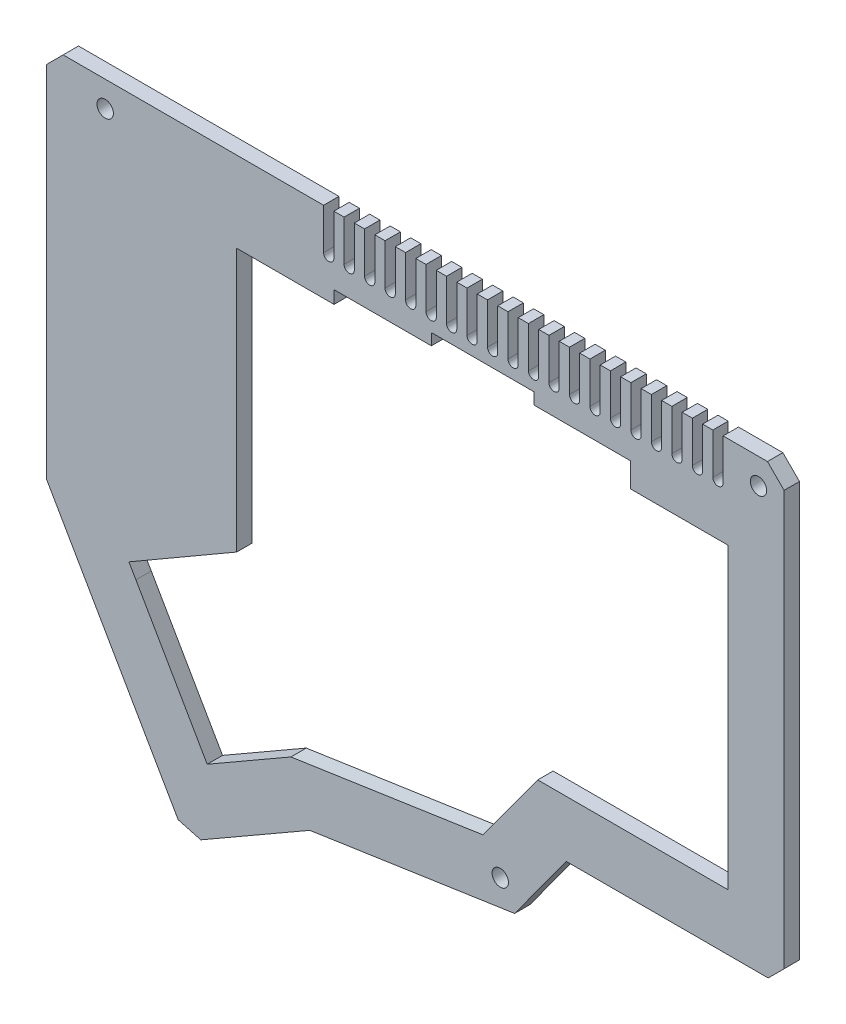
SolidWorks part; units mm, degrees
ref_plane "Plan de face" through (0, 0, 0) normal (0, 0, 1) x (1, 0, 0)
ref_plane "Plan de dessus" through (0, 0, 0) normal (0, 1, 0) x (1, 0, 0)
ref_plane "Plan de droite" through (0, 0, 0) normal (1, 0, 0) x (0, 0, -1)
sketch "Esquisse1" plane through (0, 0, 0) normal (0, 0, 1) x (1, 0, 0)
  line L0 (-117.3419, -15.4198) -> (-103.3409, -15.4198) construction
  line L1 (-103.3409, -15.4198) -> (-103.3409, -29.4208) construction
  line L2 (-103.3409, -29.4208) -> (-117.3419, -29.4208) construction
  line L3 (-117.3419, -29.4208) -> (-117.3419, -15.4198) construction
  line L4 (-98.3406, -27.0457) -> (-98.3406, -13.0447) construction
  line L5 (-98.3406, -13.0447) -> (-84.3396, -13.0447) construction
  line L6 (-84.3396, -13.0447) -> (-84.3396, -27.0457) construction
  line L7 (-84.3396, -27.0457) -> (-98.3406, -27.0457) construction
  line L8 (-79.3392, -24.6705) -> (-79.3392, -10.6695) construction
  line L9 (-79.3392, -10.6695) -> (-65.3382, -10.6695) construction
  line L10 (-65.3382, -10.6695) -> (-65.3382, -24.6705) construction
  line L11 (-65.3382, -24.6705) -> (-79.3392, -24.6705) construction
  line L12 (-60.3379, -27.0457) -> (-60.3379, -13.0447) construction
  line L13 (-60.3379, -13.0447) -> (-46.3369, -13.0447) construction
  line L14 (-46.3369, -13.0447) -> (-46.3369, -27.0457) construction
  line L15 (-46.3369, -27.0457) -> (-60.3379, -27.0457) construction
  line L16 (-41.3365, -31.796) -> (-41.3365, -17.795) construction
  line L17 (-41.3365, -17.795) -> (-27.3355, -17.795) construction
  line L18 (-27.3355, -17.795) -> (-27.3355, -31.796) construction
  line L19 (-27.3355, -31.796) -> (-41.3365, -31.796) construction
  line L20 (-22.3347, -31.796) -> (-22.3347, -17.795) construction
  line L21 (-22.3347, -17.795) -> (-8.3337, -17.795) construction
  line L22 (-8.3337, -17.795) -> (-8.3337, -31.796) construction
  line L23 (-8.3337, -31.796) -> (-22.3347, -31.796) construction
  line L24 (-117.3419, -34.4212) -> (-103.3409, -34.4212) construction
  line L25 (-103.3409, -34.4212) -> (-103.3409, -48.4222) construction
  line L26 (-103.3409, -48.4222) -> (-117.3419, -48.4222) construction
  line L27 (-117.3419, -48.4222) -> (-117.3419, -34.4212) construction
  line L28 (-98.3406, -32.046) -> (-84.3396, -32.046) construction
  line L29 (-84.3396, -32.046) -> (-84.3396, -46.047) construction
  line L30 (-84.3396, -46.047) -> (-98.3406, -46.047) construction
  line L31 (-98.3406, -46.047) -> (-98.3406, -32.046) construction
  line L32 (-79.3392, -29.6709) -> (-65.3382, -29.6709) construction
  line L33 (-65.3382, -29.6709) -> (-65.3382, -43.6718) construction
  line L34 (-65.3382, -43.6718) -> (-79.3392, -43.6718) construction
  line L35 (-79.3392, -43.6718) -> (-79.3392, -29.6709) construction
  line L36 (-60.3379, -32.046) -> (-46.3369, -32.046) construction
  line L37 (-46.3369, -32.046) -> (-46.3369, -46.047) construction
  line L38 (-46.3369, -46.047) -> (-60.3379, -46.047) construction
  line L39 (-60.3379, -46.047) -> (-60.3379, -32.046) construction
  line L40 (-41.3365, -36.7964) -> (-27.3355, -36.7964) construction
  line L41 (-27.3355, -36.7964) -> (-27.3355, -50.7973) construction
  line L42 (-27.3355, -50.7973) -> (-41.3365, -50.7973) construction
  line L43 (-41.3365, -50.7973) -> (-41.3365, -36.7964) construction
  line L44 (-22.3347, -36.7964) -> (-8.3337, -36.7964) construction
  line L45 (-8.3337, -36.7964) -> (-8.3337, -50.7973) construction
  line L46 (-8.3337, -50.7973) -> (-22.3347, -50.7973) construction
  line L47 (-22.3347, -50.7973) -> (-22.3347, -36.7964) construction
  line L48 (-22.3347, -55.7977) -> (-8.3337, -55.7977) construction
  line L49 (-8.3337, -55.7977) -> (-8.3337, -69.7987) construction
  line L50 (-8.3337, -69.7987) -> (-22.3347, -69.7987) construction
  line L51 (-22.3347, -69.7987) -> (-22.3347, -55.7977) construction
  line L52 (-41.3365, -55.7977) -> (-27.3355, -55.7977) construction
  line L53 (-27.3355, -55.7977) -> (-27.3355, -69.7987) construction
  line L54 (-27.3355, -69.7987) -> (-41.3365, -69.7987) construction
  line L55 (-41.3365, -69.7987) -> (-41.3365, -55.7977) construction
  line L56 (-60.3379, -51.0474) -> (-46.3369, -51.0474) construction
  line L57 (-46.3369, -51.0474) -> (-46.3369, -65.0484) construction
  line L58 (-46.3369, -65.0484) -> (-60.3379, -65.0484) construction
  line L59 (-60.3379, -65.0484) -> (-60.3379, -51.0474) construction
  line L60 (-79.3392, -48.6722) -> (-65.3382, -48.6722) construction
  line L61 (-65.3382, -48.6722) -> (-65.3382, -62.6732) construction
  line L62 (-65.3382, -62.6732) -> (-79.3392, -62.6732) construction
  line L63 (-79.3392, -62.6732) -> (-79.3392, -48.6722) construction
  line L64 (-98.3406, -51.0474) -> (-84.3396, -51.0474) construction
  line L65 (-84.3396, -51.0474) -> (-84.3396, -65.0484) construction
  line L66 (-84.3396, -65.0484) -> (-98.3406, -65.0484) construction
  line L67 (-98.3406, -65.0484) -> (-98.3406, -51.0474) construction
  line L68 (-117.3419, -53.4225) -> (-103.3409, -53.4225) construction
  line L69 (-103.3409, -53.4225) -> (-103.3409, -67.4235) construction
  line L70 (-103.3409, -67.4235) -> (-117.3419, -67.4235) construction
  line L71 (-117.3419, -67.4235) -> (-117.3419, -53.4225) construction
  line L72 (-88.8399, -70.6738) -> (-74.8389, -70.6738) construction
  line L73 (-74.8389, -70.6738) -> (-74.8389, -84.6747) construction
  line L74 (-74.8389, -84.6747) -> (-88.8399, -84.6747) construction
  line L75 (-88.8399, -84.6747) -> (-88.8399, -70.6738) construction
  line L76 (-111.4175, -75.4665) -> (-97.8899, -71.8565) construction
  line L77 (-97.8899, -71.8565) -> (-94.28, -85.3841) construction
  line L78 (-94.28, -85.3841) -> (-107.8075, -88.9941) construction
  line L79 (-107.8075, -88.9941) -> (-111.4175, -75.4665) construction
  line L80 (-134.6581, -81.5997) -> (-122.5281, -74.6075) construction
  line L81 (-122.5281, -74.6075) -> (-115.5359, -86.7375) construction
  line L82 (-115.5359, -86.7375) -> (-127.6659, -93.7297) construction
  line L83 (-127.6659, -93.7297) -> (-134.6581, -81.5997) construction
  line L86 (-6.475, -71.9336) -> (-62.0853, -71.9336) construction
  line L89 (-72.824, -86.6446) -> (-62.0853, -71.9336) construction
  line L96 (-109.7697, -91.4639) -> (-73.0906, -86.6918) construction
  line L97 (-124.664, -99.8297) -> (-110.3971, -91.5881) construction
  line L98 (-139.9408, -76.5013) -> (-126.7151, -99.4281) construction
  line L99 (-119.8527, -15.5421) -> (-139.6028, -15.5421) construction
  line L100 (-100.8528, -13.2921) -> (-118.8527, -13.2921) construction
  line L101 (-63.8455, -8.5421) -> (-80.8528, -8.5421) construction
  line L102 (-44.8455, -10.792) -> (-62.8485, -10.792) construction
  line L103 (-25.8456, -15.5421) -> (-43.8486, -15.5421) construction
  line L104 (-6.8456, -15.5421) -> (-23.8529, -15.5421) construction
  line L105 (-6.2741, -71.3672) -> (-6.2741, -16.1136) construction
  line L106 (-23.8529, -71.9423) -> (-6.8456, -71.9423) construction
  line L107 (-61.8455, -71.9423) -> (-25.8456, -71.9423) construction
  line L108 (-72.6738, -86.4911) -> (-62.1363, -72.0583) construction
  line L109 (-140.1743, -16.1136) -> (-140.1743, -75.5958) construction
  line L110 (-134.3462, 1.5705) -> (-134.3466, -55.7217) construction
  line L111 (-134.3466, -55.7217) -> (-160.479, -70.8411) construction
  line L112 (-160.479, -70.8411) -> (-133.7613, -117.344) construction
  line L113 (-126.937, -119.1852) -> (-105.0783, -106.604) construction
  line L114 (-105.0783, -106.604) -> (-64.4097, -100.5586) construction
  line L115 (-64.4097, -100.5586) -> (-54.4636, -86.9336) construction
  line L116 (3.6609, -86.9336) -> (-54.4636, -86.9336) construction
  line L117 (-10.475, -82.0685) -> (-10.475, 1.3161) construction
  line L122 (3.525, 6.3153) -> (-96.3444, 6.3209) construction
  line L129 (8.525, -86.9336) -> (8.525, -0.6796) construction
  line L130 (-48.3431, 6.3182) -> (-96.3444, 6.3209) construction
  line L131 (-115.3458, 1.5705) -> (-134.3462, 1.5705) construction
  line L132 (-160.479, -3.4295) -> (-160.479, -70.8411) construction
  line L135 (-119.3466, -64.3728) -> (-135.695, -73.8315) construction
  line L136 (-140.0228, -76.3355) -> (-140.0228, -76.3321)
  line L138 (-160.479, -70.8411) -> (-131.2704, -121.6794) construction
  line L139 (-131.2704, -121.6794) -> (-105.0783, -106.604) construction
  line L140 (-133.7613, -117.344) -> (-126.937, -119.1852) construction
  line L142 (-10.475, 1.3161) -> (-15.475, 6.3164) construction
  line L143 (8.525, -86.9336) -> (-54.4636, -86.9336) construction
  line L144 (-10.475, -82.0685) -> (-15.3391, -86.9326) construction
  line L148 (-103.3409, 6.3209) -> (-119.3463, 6.3209) construction
  line L149 (-119.3463, 6.3209) -> (-119.3463, 1.5705) construction
  line L150 (-140.0228, 1.5705) -> (-140.0228, 6.3209) construction
  line L151 (-140.0228, 6.3209) -> (-155.479, 6.3209) construction
  line L152 (-160.479, 1.3209) -> (-160.479, -3.4295) construction
  line L153 (-155.479, 6.3209) -> (-160.479, 1.3209) construction
  line L154 (8.525, -1.685) -> (-119.3463, -1.6779) construction
  line L155 (-146.0924, -79.8227) -> (-128.3223, -110.752) construction
  line L156 (-128.3223, -110.752) -> (-107.7547, -98.9139) construction
  line L157 (-140.0228, -78.3428) -> (-126.1111, -102.5565)
  line L158 (-126.1111, -102.5565) -> (-109.762, -93.1464)
  line L159 (-109.762, -93.1464) -> (-72.2631, -87.5722)
  line L160 (-72.2631, -87.5722) -> (-61.5772, -72.9336)
  line L162 (-24.475, -72.9336) -> (-24.475, -14.6796)
  line L163 (-24.475, -14.6796) -> (-43.4777, -14.6796)
  line L164 (-43.4777, -14.6796) -> (-43.4777, -9.9293)
  line L165 (-43.4777, -9.9293) -> (-62.3431, -9.9293)
  line L166 (-62.3431, -9.9293) -> (-62.3431, -7.681)
  line L167 (-62.3431, -7.681) -> (-82.3444, -7.6799)
  line L168 (-82.3444, -7.6799) -> (-82.3444, -9.9293)
  line L169 (-82.3444, -9.9293) -> (-101.3458, -9.9293)
  line L170 (-101.3458, -9.9293) -> (-101.3458, -12.4295)
  line L171 (-101.3458, -12.4295) -> (-120.3463, -12.4295)
  line L172 (-120.3463, -12.4295) -> (-120.3466, -63.7961)
  line L173 (-120.3466, -63.7961) -> (-140.5236, -75.4699)
  line L174 (-107.7547, -98.9139) -> (-68.8973, -93.1378) construction
  line L175 (-68.8973, -93.1378) -> (-58.5285, -78.9336) construction
  line L176 (0.525, -78.9336) -> (-58.5285, -78.9336) construction
  line L177 (-18.475, -78.9336) -> (-18.475, -1.6845) construction
  line L178 (-62.3428, -1.681) -> (-82.3441, -1.6799) construction
  line L179 (0.525, -78.9336) -> (0.525, -14.6796) construction
  line L180 (-146.0228, -76.3355) -> (-146.0228, 1.5705) construction
  line L181 (-140.0228, -76.3355) -> (-140.0228, 1.5705) construction
  line L182 (-135.695, -73.8315) -> (-140.0228, -71.3355) construction
  line L185 (-16.7232, 3.3209) -> (-116.3463, 3.3209)
  line L186 (-116.3463, 3.3209) -> (-116.3463, 1.5705) construction
  line L187 (-116.3463, 1.5705) -> (-116.3466, -66.103) construction
  line L188 (-116.3466, -66.103) -> (-135.6926, -77.2961) construction
  line L189 (-135.6926, -77.2961) -> (-143.0228, -73.0684) construction
  line L190 (-143.0228, -73.0684) -> (-143.0228, 1.5705) construction
  line L191 (-143.0228, 1.5705) -> (-143.0228, 3.3209) construction
  line L192 (-143.0228, 3.3209) -> (-154.2363, 3.3209)
  line L193 (-154.2363, 3.3209) -> (-157.479, 0.0782)
  line L194 (-157.479, 0.0782) -> (-157.479, -3.4295)
  line L195 (-157.479, -3.4295) -> (-157.479, -70.0407)
  line L196 (-157.479, -70.0407) -> (-131.7794, -114.7715)
  line L197 (-131.7794, -114.7715) -> (-127.3559, -115.9649)
  line L198 (-127.3559, -115.9649) -> (-106.082, -103.7202)
  line L199 (-106.082, -103.7202) -> (-66.0925, -97.7758)
  line L200 (-66.0925, -97.7758) -> (-55.988, -83.9336)
  line L201 (-16.5817, -83.9336) -> (-55.988, -83.9336)
  line L202 (-13.475, -80.8269) -> (-16.5817, -83.9336)
  line L203 (-13.475, -80.8269) -> (-13.475, 0.0724)
  line L204 (-13.475, 0.0724) -> (-16.7232, 3.3209)
  line L205 (-143.0228, 3.3209) -> (-140.0228, 3.3209)
  line L206 (-140.8899, -76.8336) -> (-119.3466, -64.3728) construction
  line L207 (-140.0228, -71.3355) -> (-140.0228, 1.5705) construction
  line L208 (-119.3463, 3.3209) -> (-116.3463, 3.3209)
  line L209 (-140.8899, -76.8336) -> (-126.1111, -102.5565) construction
  line L210 (-119.3463, 1.5705) -> (-119.3466, -64.3728) construction
  line L211 (-101.3458, -12.4295) -> (-120.3463, -12.4295) construction
  line L212 (-119.3463, 3.3209) -> (-140.0228, 3.3209)
  line L213 (-120.3463, -12.4295) -> (-120.3466, -64.3728) construction
  line L217 (-6.475, -71.9336) -> (-6.475, -15.6796) construction
  line L220 (-6.475, -15.6796) -> (-44.4777, -15.6796) construction
  line L221 (-44.4777, -15.6796) -> (-44.4777, -10.9293) construction
  line L222 (-44.4777, -10.9293) -> (-63.3431, -10.9293) construction
  line L223 (-63.3431, -10.9293) -> (-63.3431, -8.681) construction
  line L224 (-63.3431, -8.681) -> (-81.3444, -8.68) construction
  line L225 (-81.3444, -8.68) -> (-81.3444, -10.9293) construction
  line L226 (-81.3444, -10.9293) -> (-100.3458, -10.9293) construction
  line L227 (-100.3458, -10.9293) -> (-100.3458, -13.4295) construction
  line L228 (-100.3458, -13.4295) -> (-119.3463, -13.4295) construction
  line L231 (-119.3463, -13.4295) -> (-119.3466, -64.3728) construction
  line L232 (-119.3466, -64.3728) -> (-140.0228, -76.3355) construction
  line L233 (-140.0228, -76.3355) -> (-125.7426, -101.1906) construction
  line L234 (-125.7426, -101.1906) -> (-110.0965, -92.1851) construction
  line L235 (-110.0965, -92.1851) -> (-72.824, -86.6446) construction
  line L236 (-140.0228, -71.3355) -> (-140.0228, -59.0058)
  line L237 (-119.8474, -63.5072) -> (-140.5236, -75.4699) construction
  line L238 (-140.5236, -75.4699) -> (-141.4072, -75.9811)
  line L239 (-141.4072, -75.9811) -> (-140.0228, -78.3428)
  line L240 (-13.475, -5.3532) -> (-25.475, -5.3532) construction
  line L241 (-6.475, 3.3159) -> (-6.475, -6.6841) construction
  line L242 (5.525, 0.0724) -> (2.2822, 3.3154) construction
  line L245 (-5.475, -72.9336) -> (-5.475, -14.6796) construction
  line L248 (8.525, -82.0695) -> (3.6609, -86.9336) construction
  line L251 (5.525, -80.8269) -> (2.4183, -83.9336) construction
  line L254 (8.525, -82.0695) -> (8.525, 1.315) construction
  line L257 (5.525, -80.8269) -> (5.525, 0.0724) construction
  line L260 (8.525, 1.315) -> (3.525, 6.3153) construction
  line L263 (-24.475, -72.9336) -> (-61.5772, -72.9336)
  line L266 (-5.475, -14.6796) -> (-43.4777, -14.6796) construction
  line L269 (2.4183, -83.9336) -> (-55.988, -83.9336) construction
  line L275 (-5.475, -72.9336) -> (-61.5772, -72.9336) construction
  line L322 (-103.3409, 3.3209) -> (-96.3445, 3.3209) construction
  line L323 (-103.3409, 3.3209) -> (-116.3463, 3.3209) construction
  line L328 (-48.3431, 4.0707) -> (-48.3431, 6.3182) construction
  line L329 (-29.4777, 4.0707) -> (-48.3431, 4.0707) construction
  line L330 (-29.4777, -0.6796) -> (-29.4777, 4.0707) construction
  line L331 (8.525, -0.6796) -> (-29.4777, -0.6796) construction
  line L332 (-115.3458, 4.0707) -> (-115.3458, 1.5705) construction
  line L333 (-96.3444, 4.0707) -> (-115.3458, 4.0707) construction
  line L334 (-96.3444, 6.3209) -> (-96.3444, 4.0707) construction
  line L343 (2.2822, 3.3154) -> (-96.3445, 3.3209) construction
  line L465 (-103.3409, 6.3209) -> (-96.3444, 6.3209) construction
  circle A2 centre (-18.475, -1.6845) radius 1.6
  circle A3 centre (-18.475, -1.6845) radius 3 construction
  circle A4 centre (-110.3971, -1.6784) radius 1.6 construction
  circle A5 centre (-18.475, -78.9336) radius 1.6 construction
  circle A6 centre (-68.8973, -93.1378) radius 1.6
  circle A7 centre (-128.3223, -110.752) radius 1.6 construction
  circle A8 centre (-146.0924, -79.8227) radius 1.6 construction
  circle A9 centre (-146.0228, -1.6779) radius 1.6
  circle A10 centre (-110.3971, -1.6784) radius 3 construction
  circle A11 centre (-146.0228, -1.6779) radius 3 construction
  circle A12 centre (-146.0924, -79.8227) radius 3 construction
  circle A13 centre (-128.3223, -110.752) radius 3 construction
  circle A14 centre (-68.8973, -93.1378) radius 3 construction
  circle A15 centre (-18.475, -78.9336) radius 3 construction
  point P138 (-160.479, 1.5705)
  point P139 (-10.475, 6.3161)
  point P150 (-160.479, 6.3209)
  dimension "D3" = 3.2
  dimension "D4" = 6
  dimension "D6" = 3.2
  dimension "D7" = 3.2
  dimension "D8" = 3.2
  dimension "D9" = 3.2
  dimension "D10" = 3.2
  dimension "D15" = 3.2
  dimension "D17" = 12
  dimension "D1" = 15
  dimension "D5" = 1
  dimension "D13" = 6
  dimension "D16" = 3
extrude "Boss.-Extru.1" add sketch "Esquisse1" along normal blind 3
sketch "Esquisse2" plane through (0, 0, 3) normal (0, 0, 1) x (1, 0, 0)
  line L19 (-26.3866, 6.0542) -> (-26.3866, -4.6791) construction
  line L20 (-25.3866, 6.0542) -> (-25.3866, -4.6791)
  line L21 (-27.3866, 6.0542) -> (-27.3866, -4.6791)
  line L22 (-30.3866, 6.0542) -> (-30.3866, -4.6791) construction
  line L23 (-29.3866, 6.0542) -> (-29.3866, -4.6791)
  line L24 (-31.3866, 6.0542) -> (-31.3866, -4.6791)
  line L25 (-34.3866, 6.0542) -> (-34.3866, -4.6791) construction
  line L26 (-33.3866, 6.0542) -> (-33.3866, -4.6791)
  line L27 (-35.3866, 6.0542) -> (-35.3866, -4.6791)
  line L28 (-38.3866, 6.0542) -> (-38.3866, -4.6791) construction
  line L29 (-37.3866, 6.0542) -> (-37.3866, -4.6791)
  line L30 (-39.3866, 6.0542) -> (-39.3866, -4.6791)
  line L31 (-42.3866, 6.0542) -> (-42.3866, -4.6791) construction
  line L32 (-41.3866, 6.0542) -> (-41.3866, -4.6791)
  line L33 (-43.3866, 6.0542) -> (-43.3866, -4.6791)
  line L34 (-46.3866, 6.0542) -> (-46.3866, -4.6791) construction
  line L35 (-45.3866, 6.0542) -> (-45.3866, -4.6791)
  line L36 (-47.3866, 6.0542) -> (-47.3866, -4.6791)
  line L37 (-50.3866, 6.0542) -> (-50.3866, -4.6791) construction
  line L38 (-49.3866, 6.0542) -> (-49.3866, -4.6791)
  line L39 (-51.3866, 6.0542) -> (-51.3866, -4.6791)
  line L40 (-54.3866, 6.0542) -> (-54.3866, -4.6791) construction
  line L41 (-53.3866, 6.0542) -> (-53.3866, -4.6791)
  line L42 (-55.3866, 6.0542) -> (-55.3866, -4.6791)
  line L43 (-58.3866, 6.0542) -> (-58.3866, -4.6791) construction
  line L44 (-57.3866, 6.0542) -> (-57.3866, -4.6791)
  line L45 (-59.3866, 6.0542) -> (-59.3866, -4.6791)
  line L46 (-62.3866, 6.0542) -> (-62.3866, -4.6791) construction
  line L47 (-61.3866, 6.0542) -> (-61.3866, -4.6791)
  line L48 (-63.3866, 6.0542) -> (-63.3866, -4.6791)
  line L49 (-66.3866, 6.0542) -> (-66.3866, -4.6791) construction
  line L50 (-65.3866, 6.0542) -> (-65.3866, -4.6791)
  line L51 (-67.3866, 6.0542) -> (-67.3866, -4.6791)
  line L52 (-70.3866, 6.0542) -> (-70.3866, -4.6791) construction
  line L53 (-69.3866, 6.0542) -> (-69.3866, -4.6791)
  line L54 (-71.3866, 6.0542) -> (-71.3866, -4.6791)
  line L55 (-74.3866, 6.0542) -> (-74.3866, -4.6791) construction
  line L56 (-73.3866, 6.0542) -> (-73.3866, -4.6791)
  line L57 (-75.3866, 6.0542) -> (-75.3866, -4.6791)
  line L58 (-78.3866, 6.0542) -> (-78.3866, -4.6791) construction
  line L59 (-77.3866, 6.0542) -> (-77.3866, -4.6791)
  line L60 (-79.3866, 6.0542) -> (-79.3866, -4.6791)
  line L61 (-82.3866, 6.0542) -> (-82.3866, -4.6791) construction
  line L62 (-81.3866, 6.0542) -> (-81.3866, -4.6791)
  line L63 (-83.3866, 6.0542) -> (-83.3866, -4.6791)
  line L64 (-86.3866, 6.0542) -> (-86.3866, -4.6791) construction
  line L65 (-85.3866, 6.0542) -> (-85.3866, -4.6791)
  line L66 (-87.3866, 6.0542) -> (-87.3866, -4.6791)
  line L67 (-90.3866, 6.0542) -> (-90.3866, -4.6791) construction
  line L68 (-89.3866, 6.0542) -> (-89.3866, -4.6791)
  line L69 (-91.3866, 6.0542) -> (-91.3866, -4.6791)
  line L70 (-94.3866, 6.0542) -> (-94.3866, -4.6791) construction
  line L71 (-93.3866, 6.0542) -> (-93.3866, -4.6791)
  line L72 (-95.3866, 6.0542) -> (-95.3866, -4.6791)
  line L73 (-98.3866, 6.0542) -> (-98.3866, -4.6791) construction
  line L74 (-97.3866, 6.0542) -> (-97.3866, -4.6791)
  line L75 (-99.3866, 6.0542) -> (-99.3866, -4.6791)
  line L76 (-102.3866, 6.0542) -> (-102.3866, -4.6791) construction
  line L77 (-101.3866, 6.0542) -> (-101.3866, -4.6791)
  line L78 (-103.3866, 6.0542) -> (-103.3866, -4.6791)
  arc A10 (-25.3866, 6.0542) -> (-27.3866, 6.0542) centre (-26.3866, 6.0542) ccw
  arc A11 (-27.3866, -4.6791) -> (-25.3866, -4.6791) centre (-26.3866, -4.6791) ccw
  arc A12 (-29.3866, 6.0542) -> (-31.3866, 6.0542) centre (-30.3866, 6.0542) ccw
  arc A13 (-31.3866, -4.6791) -> (-29.3866, -4.6791) centre (-30.3866, -4.6791) ccw
  arc A14 (-33.3866, 6.0542) -> (-35.3866, 6.0542) centre (-34.3866, 6.0542) ccw
  arc A15 (-35.3866, -4.6791) -> (-33.3866, -4.6791) centre (-34.3866, -4.6791) ccw
  arc A16 (-37.3866, 6.0542) -> (-39.3866, 6.0542) centre (-38.3866, 6.0542) ccw
  arc A17 (-39.3866, -4.6791) -> (-37.3866, -4.6791) centre (-38.3866, -4.6791) ccw
  arc A18 (-41.3866, 6.0542) -> (-43.3866, 6.0542) centre (-42.3866, 6.0542) ccw
  arc A19 (-43.3866, -4.6791) -> (-41.3866, -4.6791) centre (-42.3866, -4.6791) ccw
  arc A20 (-45.3866, 6.0542) -> (-47.3866, 6.0542) centre (-46.3866, 6.0542) ccw
  arc A21 (-47.3866, -4.6791) -> (-45.3866, -4.6791) centre (-46.3866, -4.6791) ccw
  arc A22 (-49.3866, 6.0542) -> (-51.3866, 6.0542) centre (-50.3866, 6.0542) ccw
  arc A23 (-51.3866, -4.6791) -> (-49.3866, -4.6791) centre (-50.3866, -4.6791) ccw
  arc A24 (-53.3866, 6.0542) -> (-55.3866, 6.0542) centre (-54.3866, 6.0542) ccw
  arc A25 (-55.3866, -4.6791) -> (-53.3866, -4.6791) centre (-54.3866, -4.6791) ccw
  arc A26 (-57.3866, 6.0542) -> (-59.3866, 6.0542) centre (-58.3866, 6.0542) ccw
  arc A27 (-59.3866, -4.6791) -> (-57.3866, -4.6791) centre (-58.3866, -4.6791) ccw
  arc A28 (-61.3866, 6.0542) -> (-63.3866, 6.0542) centre (-62.3866, 6.0542) ccw
  arc A29 (-63.3866, -4.6791) -> (-61.3866, -4.6791) centre (-62.3866, -4.6791) ccw
  arc A30 (-65.3866, 6.0542) -> (-67.3866, 6.0542) centre (-66.3866, 6.0542) ccw
  arc A31 (-67.3866, -4.6791) -> (-65.3866, -4.6791) centre (-66.3866, -4.6791) ccw
  arc A32 (-69.3866, 6.0542) -> (-71.3866, 6.0542) centre (-70.3866, 6.0542) ccw
  arc A33 (-71.3866, -4.6791) -> (-69.3866, -4.6791) centre (-70.3866, -4.6791) ccw
  arc A34 (-73.3866, 6.0542) -> (-75.3866, 6.0542) centre (-74.3866, 6.0542) ccw
  arc A35 (-75.3866, -4.6791) -> (-73.3866, -4.6791) centre (-74.3866, -4.6791) ccw
  arc A36 (-77.3866, 6.0542) -> (-79.3866, 6.0542) centre (-78.3866, 6.0542) ccw
  arc A37 (-79.3866, -4.6791) -> (-77.3866, -4.6791) centre (-78.3866, -4.6791) ccw
  arc A38 (-81.3866, 6.0542) -> (-83.3866, 6.0542) centre (-82.3866, 6.0542) ccw
  arc A39 (-83.3866, -4.6791) -> (-81.3866, -4.6791) centre (-82.3866, -4.6791) ccw
  arc A40 (-85.3866, 6.0542) -> (-87.3866, 6.0542) centre (-86.3866, 6.0542) ccw
  arc A41 (-87.3866, -4.6791) -> (-85.3866, -4.6791) centre (-86.3866, -4.6791) ccw
  arc A42 (-89.3866, 6.0542) -> (-91.3866, 6.0542) centre (-90.3866, 6.0542) ccw
  arc A43 (-91.3866, -4.6791) -> (-89.3866, -4.6791) centre (-90.3866, -4.6791) ccw
  arc A44 (-93.3866, 6.0542) -> (-95.3866, 6.0542) centre (-94.3866, 6.0542) ccw
  arc A45 (-95.3866, -4.6791) -> (-93.3866, -4.6791) centre (-94.3866, -4.6791) ccw
  arc A46 (-97.3866, 6.0542) -> (-99.3866, 6.0542) centre (-98.3866, 6.0542) ccw
  arc A47 (-99.3866, -4.6791) -> (-97.3866, -4.6791) centre (-98.3866, -4.6791) ccw
  arc A48 (-101.3866, 6.0542) -> (-103.3866, 6.0542) centre (-102.3866, 6.0542) ccw
  arc A49 (-103.3866, -4.6791) -> (-101.3866, -4.6791) centre (-102.3866, -4.6791) ccw
  point P45 (-26.3866, 0.6875)
  point P52 (-30.3866, 0.6875)
  point P59 (-34.3866, 0.6875)
  point P66 (-38.3866, 0.6875)
  point P73 (-42.3866, 0.6875)
  point P80 (-46.3866, 0.6875)
  point P87 (-50.3866, 0.6875)
  point P94 (-54.3866, 0.6875)
  point P101 (-58.3866, 0.6875)
  point P108 (-62.3866, 0.6875)
  point P115 (-66.3866, 0.6875)
  point P122 (-70.3866, 0.6875)
  point P129 (-74.3866, 0.6875)
  point P136 (-78.3866, 0.6875)
  point P143 (-82.3866, 0.6875)
  point P150 (-86.3866, 0.6875)
  point P157 (-90.3866, 0.6875)
  point P164 (-94.3866, 0.6875)
  point P171 (-98.3866, 0.6875)
  point P178 (-102.3866, 0.6875)
extrude "Enlèv. mat.-Extru.1" cut sketch "Esquisse2" against normal blind 10
sketch "Esquisse3" plane through (0, 0, 3) normal (0, 0, 1) x (1, 0, 0)
  line L18 (-61.5772, -72.9336) -> (-24.475, -72.9336)
  line L19 (-141.4072, -75.9811) -> (-140.0228, -78.3428)
  line L20 (-120.3466, -63.7961) -> (-141.4072, -75.9811)
  line L21 (-120.3463, -12.4295) -> (-120.3466, -63.7961)
  line L22 (-101.3458, -12.4295) -> (-120.3463, -12.4295)
  line L23 (-101.3458, -9.9293) -> (-101.3458, -12.4295)
  line L24 (-82.3444, -9.9293) -> (-101.3458, -9.9293)
  line L25 (-82.3444, -7.6799) -> (-82.3444, -9.9293)
  line L26 (-62.3431, -7.681) -> (-82.3444, -7.6799)
  line L27 (-62.3431, -9.9293) -> (-62.3431, -7.681)
  line L28 (-43.4777, -9.9293) -> (-62.3431, -9.9293)
  line L29 (-43.4777, -14.6796) -> (-43.4777, -9.9293)
  line L30 (-24.475, -14.6796) -> (-43.4777, -14.6796)
  line L31 (-24.475, -72.9336) -> (-24.475, -14.6796)
  line L32 (-61.5772, -72.9336) -> (-24.475, -72.9336)
  line L33 (-72.2631, -87.5722) -> (-61.5772, -72.9336)
  line L34 (-109.762, -93.1464) -> (-72.2631, -87.5722)
  line L35 (-126.1111, -102.5565) -> (-109.762, -93.1464)
  line L36 (-140.0228, -78.3428) -> (-126.1111, -102.5565)
  line L37 (-141.4072, -75.9811) -> (-140.0228, -78.3428)
  line L38 (-120.3466, -63.7961) -> (-141.4072, -75.9811)
  line L39 (-120.3463, -12.4295) -> (-120.3466, -63.7961)
  line L40 (-101.3458, -12.4295) -> (-120.3463, -12.4295)
  line L41 (-101.3458, -9.9293) -> (-101.3458, -12.4295)
  line L42 (-82.3444, -9.9293) -> (-101.3458, -9.9293)
  line L43 (-82.3444, -7.6799) -> (-82.3444, -9.9293)
  line L44 (-62.3431, -7.681) -> (-82.3444, -7.6799)
  line L45 (-62.3431, -9.9293) -> (-62.3431, -7.681)
  line L46 (-43.4777, -9.9293) -> (-62.3431, -9.9293)
  line L47 (-43.4777, -14.6796) -> (-43.4777, -9.9293)
  line L48 (-24.475, -14.6796) -> (-43.4777, -14.6796)
  line L49 (-24.475, -72.9336) -> (-24.475, -14.6796)
  line L51 (-72.2631, -87.5722) -> (-61.5772, -72.9336)
  line L52 (-109.762, -93.1464) -> (-72.2631, -87.5722)
  line L53 (-126.1111, -102.5565) -> (-109.762, -93.1464)
  line L54 (-140.0228, -78.3428) -> (-126.1111, -102.5565)
  line L101 (-16.7232, 3.3209) -> (-25.3866, 3.3209)
  line L102 (-25.3866, 3.3209) -> (-25.3866, -4.6791)
  line L103 (-27.3866, -4.6791) -> (-27.3866, 3.3209)
  line L104 (-27.3866, 3.3209) -> (-29.3866, 3.3209)
  line L105 (-29.3866, 3.3209) -> (-29.3866, -4.6791)
  line L106 (-31.3866, -4.6791) -> (-31.3866, 3.3209)
  line L107 (-31.3866, 3.3209) -> (-33.3866, 3.3209)
  line L108 (-33.3866, 3.3209) -> (-33.3866, -4.6791)
  line L109 (-35.3866, -4.6791) -> (-35.3866, 3.3209)
  line L110 (-35.3866, 3.3209) -> (-37.3866, 3.3209)
  line L111 (-37.3866, 3.3209) -> (-37.3866, -4.6791)
  line L112 (-39.3866, -4.6791) -> (-39.3866, 3.3209)
  line L113 (-39.3866, 3.3209) -> (-41.3866, 3.3209)
  line L114 (-41.3866, 3.3209) -> (-41.3866, -4.6791)
  line L115 (-43.3866, -4.6791) -> (-43.3866, 3.3209)
  line L116 (-43.3866, 3.3209) -> (-45.3866, 3.3209)
  line L117 (-45.3866, 3.3209) -> (-45.3866, -4.6791)
  line L118 (-47.3866, -4.6791) -> (-47.3866, 3.3209)
  line L119 (-47.3866, 3.3209) -> (-49.3866, 3.3209)
  line L120 (-49.3866, 3.3209) -> (-49.3866, -4.6791)
  line L121 (-51.3866, -4.6791) -> (-51.3866, 3.3209)
  line L122 (-51.3866, 3.3209) -> (-53.3866, 3.3209)
  line L123 (-53.3866, 3.3209) -> (-53.3866, -4.6791)
  line L124 (-55.3866, -4.6791) -> (-55.3866, 3.3209)
  line L125 (-55.3866, 3.3209) -> (-57.3866, 3.3209)
  line L126 (-57.3866, 3.3209) -> (-57.3866, -4.6791)
  line L127 (-59.3866, -4.6791) -> (-59.3866, 3.3209)
  line L128 (-59.3866, 3.3209) -> (-61.3866, 3.3209)
  line L129 (-61.3866, 3.3209) -> (-61.3866, -4.6791)
  line L130 (-63.3866, -4.6791) -> (-63.3866, 3.3209)
  line L131 (-63.3866, 3.3209) -> (-65.3866, 3.3209)
  line L132 (-65.3866, 3.3209) -> (-65.3866, -4.6791)
  line L133 (-67.3866, -4.6791) -> (-67.3866, 3.3209)
  line L134 (-67.3866, 3.3209) -> (-69.3866, 3.3209)
  line L135 (-69.3866, 3.3209) -> (-69.3866, -4.6791)
  line L136 (-71.3866, -4.6791) -> (-71.3866, 3.3209)
  line L137 (-71.3866, 3.3209) -> (-73.3866, 3.3209)
  line L138 (-73.3866, 3.3209) -> (-73.3866, -4.6791)
  line L139 (-75.3866, -4.6791) -> (-75.3866, 3.3209)
  line L140 (-75.3866, 3.3209) -> (-77.3866, 3.3209)
  line L141 (-77.3866, 3.3209) -> (-77.3866, -4.6791)
  line L142 (-79.3866, -4.6791) -> (-79.3866, 3.3209)
  line L143 (-79.3866, 3.3209) -> (-81.3866, 3.3209)
  line L144 (-81.3866, 3.3209) -> (-81.3866, -4.6791)
  line L145 (-83.3866, -4.6791) -> (-83.3866, 3.3209)
  line L146 (-83.3866, 3.3209) -> (-85.3866, 3.3209)
  line L147 (-85.3866, 3.3209) -> (-85.3866, -4.6791)
  line L148 (-87.3866, -4.6791) -> (-87.3866, 3.3209)
  line L149 (-87.3866, 3.3209) -> (-89.3866, 3.3209)
  line L150 (-89.3866, 3.3209) -> (-89.3866, -4.6791)
  line L151 (-91.3866, -4.6791) -> (-91.3866, 3.3209)
  line L152 (-91.3866, 3.3209) -> (-93.3866, 3.3209)
  line L153 (-93.3866, 3.3209) -> (-93.3866, -4.6791)
  line L154 (-95.3866, -4.6791) -> (-95.3866, 3.3209)
  line L155 (-95.3866, 3.3209) -> (-97.3866, 3.3209)
  line L156 (-97.3866, 3.3209) -> (-97.3866, -4.6791)
  line L157 (-99.3866, -4.6791) -> (-99.3866, 3.3209)
  line L158 (-99.3866, 3.3209) -> (-101.3866, 3.3209)
  line L159 (-101.3866, 3.3209) -> (-101.3866, -4.6791)
  line L160 (-103.3866, -4.6791) -> (-103.3866, 3.3209)
  line L161 (-103.3866, 3.3209) -> (-154.2363, 3.3209)
  line L162 (-154.2363, 3.3209) -> (-157.479, 0.0782)
  line L163 (-157.479, 0.0782) -> (-157.479, -70.0407)
  line L164 (-157.479, -70.0407) -> (-131.7794, -114.7715)
  line L165 (-131.7794, -114.7715) -> (-127.3559, -115.9649)
  line L166 (-127.3559, -115.9649) -> (-106.082, -103.7202)
  line L167 (-106.082, -103.7202) -> (-66.0925, -97.7758)
  line L168 (-66.0925, -97.7758) -> (-55.988, -83.9336)
  line L169 (-55.988, -83.9336) -> (-16.5817, -83.9336)
  line L170 (-16.5817, -83.9336) -> (-13.475, -80.8269)
  line L171 (-13.475, -80.8269) -> (-13.475, 0.0724)
  line L172 (-13.475, 0.0724) -> (-16.7232, 3.3209)
  line L188 (-16.7232, 3.3209) -> (-25.3866, 3.3209)
  line L189 (-25.3866, 3.3209) -> (-25.3866, -4.6791)
  line L190 (-27.3866, -4.6791) -> (-27.3866, 3.3209)
  line L191 (-27.3866, 3.3209) -> (-29.3866, 3.3209)
  line L192 (-29.3866, 3.3209) -> (-29.3866, -4.6791)
  line L193 (-31.3866, -4.6791) -> (-31.3866, 3.3209)
  line L194 (-31.3866, 3.3209) -> (-33.3866, 3.3209)
  line L195 (-33.3866, 3.3209) -> (-33.3866, -4.6791)
  line L196 (-35.3866, -4.6791) -> (-35.3866, 3.3209)
  line L197 (-35.3866, 3.3209) -> (-37.3866, 3.3209)
  line L198 (-37.3866, 3.3209) -> (-37.3866, -4.6791)
  line L199 (-39.3866, -4.6791) -> (-39.3866, 3.3209)
  line L200 (-39.3866, 3.3209) -> (-41.3866, 3.3209)
  line L201 (-41.3866, 3.3209) -> (-41.3866, -4.6791)
  line L202 (-43.3866, -4.6791) -> (-43.3866, 3.3209)
  line L203 (-43.3866, 3.3209) -> (-45.3866, 3.3209)
  line L204 (-45.3866, 3.3209) -> (-45.3866, -4.6791)
  line L205 (-47.3866, -4.6791) -> (-47.3866, 3.3209)
  line L206 (-47.3866, 3.3209) -> (-49.3866, 3.3209)
  line L207 (-49.3866, 3.3209) -> (-49.3866, -4.6791)
  line L208 (-51.3866, -4.6791) -> (-51.3866, 3.3209)
  line L209 (-51.3866, 3.3209) -> (-53.3866, 3.3209)
  line L210 (-53.3866, 3.3209) -> (-53.3866, -4.6791)
  line L211 (-55.3866, -4.6791) -> (-55.3866, 3.3209)
  line L212 (-55.3866, 3.3209) -> (-57.3866, 3.3209)
  line L213 (-57.3866, 3.3209) -> (-57.3866, -4.6791)
  line L214 (-59.3866, -4.6791) -> (-59.3866, 3.3209)
  line L215 (-59.3866, 3.3209) -> (-61.3866, 3.3209)
  line L216 (-61.3866, 3.3209) -> (-61.3866, -4.6791)
  line L217 (-63.3866, -4.6791) -> (-63.3866, 3.3209)
  line L218 (-63.3866, 3.3209) -> (-65.3866, 3.3209)
  line L219 (-65.3866, 3.3209) -> (-65.3866, -4.6791)
  line L220 (-67.3866, -4.6791) -> (-67.3866, 3.3209)
  line L221 (-67.3866, 3.3209) -> (-69.3866, 3.3209)
  line L222 (-69.3866, 3.3209) -> (-69.3866, -4.6791)
  line L223 (-71.3866, -4.6791) -> (-71.3866, 3.3209)
  line L224 (-71.3866, 3.3209) -> (-73.3866, 3.3209)
  line L225 (-73.3866, 3.3209) -> (-73.3866, -4.6791)
  line L226 (-75.3866, -4.6791) -> (-75.3866, 3.3209)
  line L227 (-75.3866, 3.3209) -> (-77.3866, 3.3209)
  line L228 (-77.3866, 3.3209) -> (-77.3866, -4.6791)
  line L229 (-79.3866, -4.6791) -> (-79.3866, 3.3209)
  line L230 (-79.3866, 3.3209) -> (-81.3866, 3.3209)
  line L231 (-81.3866, 3.3209) -> (-81.3866, -4.6791)
  line L232 (-83.3866, -4.6791) -> (-83.3866, 3.3209)
  line L233 (-83.3866, 3.3209) -> (-85.3866, 3.3209)
  line L234 (-85.3866, 3.3209) -> (-85.3866, -4.6791)
  line L235 (-87.3866, -4.6791) -> (-87.3866, 3.3209)
  line L236 (-87.3866, 3.3209) -> (-89.3866, 3.3209)
  line L237 (-89.3866, 3.3209) -> (-89.3866, -4.6791)
  line L238 (-91.3866, -4.6791) -> (-91.3866, 3.3209)
  line L239 (-91.3866, 3.3209) -> (-93.3866, 3.3209)
  line L240 (-93.3866, 3.3209) -> (-93.3866, -4.6791)
  line L241 (-95.3866, -4.6791) -> (-95.3866, 3.3209)
  line L242 (-95.3866, 3.3209) -> (-97.3866, 3.3209)
  line L243 (-97.3866, 3.3209) -> (-97.3866, -4.6791)
  line L244 (-99.3866, -4.6791) -> (-99.3866, 3.3209)
  line L245 (-99.3866, 3.3209) -> (-101.3866, 3.3209)
  line L246 (-101.3866, 3.3209) -> (-101.3866, -4.6791)
  line L247 (-103.3866, -4.6791) -> (-103.3866, 3.3209)
  line L248 (-103.3866, 3.3209) -> (-154.2363, 3.3209)
  line L249 (-154.2363, 3.3209) -> (-157.479, 0.0782)
  line L250 (-157.479, 0.0782) -> (-157.479, -70.0407)
  line L251 (-157.479, -70.0407) -> (-131.7794, -114.7715)
  line L252 (-131.7794, -114.7715) -> (-127.3559, -115.9649)
  line L253 (-127.3559, -115.9649) -> (-106.082, -103.7202)
  line L254 (-106.082, -103.7202) -> (-66.0925, -97.7758)
  line L255 (-66.0925, -97.7758) -> (-55.988, -83.9336)
  line L256 (-55.988, -83.9336) -> (-16.5817, -83.9336)
  line L257 (-16.5817, -83.9336) -> (-13.475, -80.8269)
  line L258 (-13.475, -80.8269) -> (-13.475, 0.0724)
  line L259 (-13.475, 0.0724) -> (-16.7232, 3.3209)
  circle A0 centre (-68.8973, -93.1378) radius 1.6 construction
  circle A1 centre (-18.475, -1.6845) radius 1.6 construction
  circle A2 centre (-146.0228, -1.6779) radius 1.6 construction
  circle A3 centre (-68.8973, -93.1378) radius 1.6
  circle A4 centre (-18.475, -1.6845) radius 1.6
  circle A5 centre (-146.0228, -1.6779) radius 1.6
  arc A30 (-27.3866, -4.6791) -> (-25.3866, -4.6791) centre (-26.3866, -4.6791) ccw
  arc A31 (-31.3866, -4.6791) -> (-29.3866, -4.6791) centre (-30.3866, -4.6791) ccw
  arc A32 (-35.3866, -4.6791) -> (-33.3866, -4.6791) centre (-34.3866, -4.6791) ccw
  arc A33 (-39.3866, -4.6791) -> (-37.3866, -4.6791) centre (-38.3866, -4.6791) ccw
  arc A34 (-43.3866, -4.6791) -> (-41.3866, -4.6791) centre (-42.3866, -4.6791) ccw
  arc A35 (-47.3866, -4.6791) -> (-45.3866, -4.6791) centre (-46.3866, -4.6791) ccw
  arc A36 (-51.3866, -4.6791) -> (-49.3866, -4.6791) centre (-50.3866, -4.6791) ccw
  arc A37 (-55.3866, -4.6791) -> (-53.3866, -4.6791) centre (-54.3866, -4.6791) ccw
  arc A38 (-59.3866, -4.6791) -> (-57.3866, -4.6791) centre (-58.3866, -4.6791) ccw
  arc A39 (-63.3866, -4.6791) -> (-61.3866, -4.6791) centre (-62.3866, -4.6791) ccw
  arc A40 (-67.3866, -4.6791) -> (-65.3866, -4.6791) centre (-66.3866, -4.6791) ccw
  arc A41 (-71.3866, -4.6791) -> (-69.3866, -4.6791) centre (-70.3866, -4.6791) ccw
  arc A42 (-75.3866, -4.6791) -> (-73.3866, -4.6791) centre (-74.3866, -4.6791) ccw
  arc A43 (-79.3866, -4.6791) -> (-77.3866, -4.6791) centre (-78.3866, -4.6791) ccw
  arc A44 (-83.3866, -4.6791) -> (-81.3866, -4.6791) centre (-82.3866, -4.6791) ccw
  arc A45 (-87.3866, -4.6791) -> (-85.3866, -4.6791) centre (-86.3866, -4.6791) ccw
  arc A46 (-91.3866, -4.6791) -> (-89.3866, -4.6791) centre (-90.3866, -4.6791) ccw
  arc A47 (-95.3866, -4.6791) -> (-93.3866, -4.6791) centre (-94.3866, -4.6791) ccw
  arc A48 (-99.3866, -4.6791) -> (-97.3866, -4.6791) centre (-98.3866, -4.6791) ccw
  arc A49 (-103.3866, -4.6791) -> (-101.3866, -4.6791) centre (-102.3866, -4.6791) ccw
  arc A55 (-27.3866, -4.6791) -> (-25.3866, -4.6791) centre (-26.3866, -4.6791) ccw
  arc A56 (-31.3866, -4.6791) -> (-29.3866, -4.6791) centre (-30.3866, -4.6791) ccw
  arc A57 (-35.3866, -4.6791) -> (-33.3866, -4.6791) centre (-34.3866, -4.6791) ccw
  arc A58 (-39.3866, -4.6791) -> (-37.3866, -4.6791) centre (-38.3866, -4.6791) ccw
  arc A59 (-43.3866, -4.6791) -> (-41.3866, -4.6791) centre (-42.3866, -4.6791) ccw
  arc A60 (-47.3866, -4.6791) -> (-45.3866, -4.6791) centre (-46.3866, -4.6791) ccw
  arc A61 (-51.3866, -4.6791) -> (-49.3866, -4.6791) centre (-50.3866, -4.6791) ccw
  arc A62 (-55.3866, -4.6791) -> (-53.3866, -4.6791) centre (-54.3866, -4.6791) ccw
  arc A63 (-59.3866, -4.6791) -> (-57.3866, -4.6791) centre (-58.3866, -4.6791) ccw
  arc A64 (-63.3866, -4.6791) -> (-61.3866, -4.6791) centre (-62.3866, -4.6791) ccw
  arc A65 (-67.3866, -4.6791) -> (-65.3866, -4.6791) centre (-66.3866, -4.6791) ccw
  arc A66 (-71.3866, -4.6791) -> (-69.3866, -4.6791) centre (-70.3866, -4.6791) ccw
  arc A67 (-75.3866, -4.6791) -> (-73.3866, -4.6791) centre (-74.3866, -4.6791) ccw
  arc A68 (-79.3866, -4.6791) -> (-77.3866, -4.6791) centre (-78.3866, -4.6791) ccw
  arc A69 (-83.3866, -4.6791) -> (-81.3866, -4.6791) centre (-82.3866, -4.6791) ccw
  arc A70 (-87.3866, -4.6791) -> (-85.3866, -4.6791) centre (-86.3866, -4.6791) ccw
  arc A71 (-91.3866, -4.6791) -> (-89.3866, -4.6791) centre (-90.3866, -4.6791) ccw
  arc A72 (-95.3866, -4.6791) -> (-93.3866, -4.6791) centre (-94.3866, -4.6791) ccw
  arc A73 (-99.3866, -4.6791) -> (-97.3866, -4.6791) centre (-98.3866, -4.6791) ccw
  arc A74 (-103.3866, -4.6791) -> (-101.3866, -4.6791) centre (-102.3866, -4.6791) ccw
  dimension "D1" = 0
  dimension "D2" = 0
